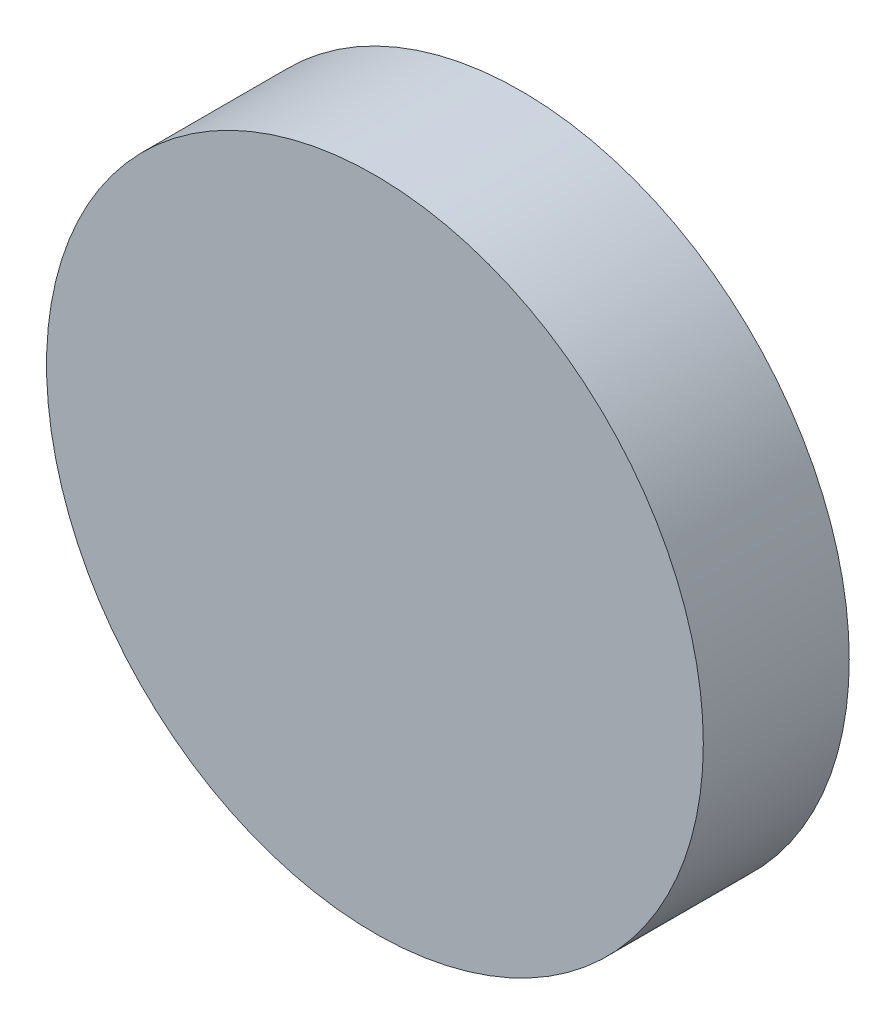
SolidWorks part; units mm, degrees
ref_plane "前视基准面" through (0, 0, 0) normal (0, 0, 1) x (1, 0, 0)
ref_plane "上视基准面" through (0, 0, 0) normal (0, 1, 0) x (1, 0, 0)
ref_plane "右视基准面" through (0, 0, 0) normal (1, 0, 0) x (0, 0, -1)
other "Configuration Table"
sketch "草图1" plane through (0, 0, 0) normal (0, 0, 1) x (1, 0, 0)
  circle A0 centre (0, 0) radius 9
  dimension "diameter" = 18
extrude "Head_and_washer_envelope" add sketch "草图1" along normal blind 4
